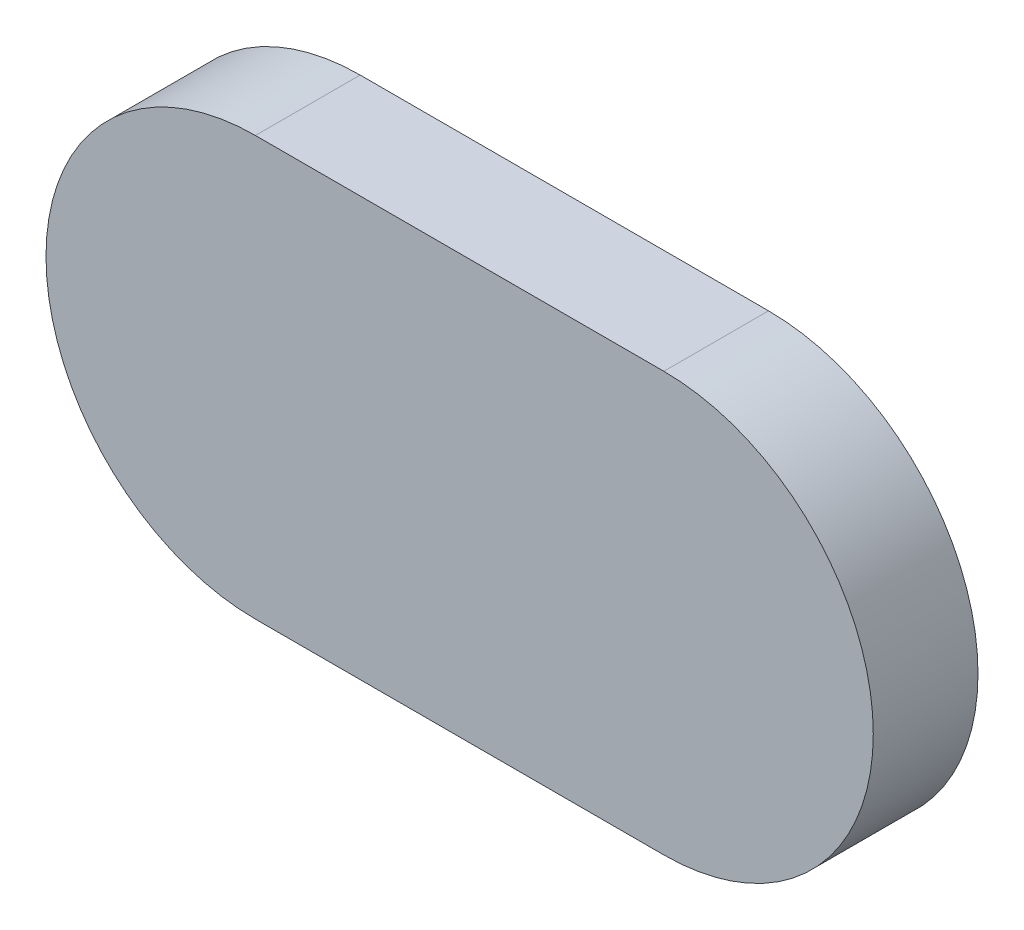
SolidWorks part; units mm, degrees
ref_plane "Спереди" through (0, 0, 0) normal (0, 0, 1) x (1, 0, 0)
ref_plane "Сверху" through (0, 0, 0) normal (0, 1, 0) x (1, 0, 0)
ref_plane "Справа" through (0, 0, 0) normal (1, 0, 0) x (0, 0, -1)
other "Configuration Table"
sketch "Эскиз1" plane through (0, 0, 0) normal (0, 0, 1) x (1, 0, 0)
  line L0 (-19.5, 0) -> (19.5, 0) construction
  line L2 (-19.5, 20) -> (19.5, 20)
  line L3 (-19.5, -20) -> (19.5, -20)
  arc A0 (-19.5, 20) -> (-19.5, -20) centre (-19.5, 0) ccw
  arc A1 (19.5, -20) -> (19.5, 20) centre (19.5, 0) ccw
  point P5 (0, 0)
  dimension "D1" = 40
  dimension "D2" = 39
extrude "Бобышка-Вытянуть1" add sketch "Эскиз1" along normal blind 10
